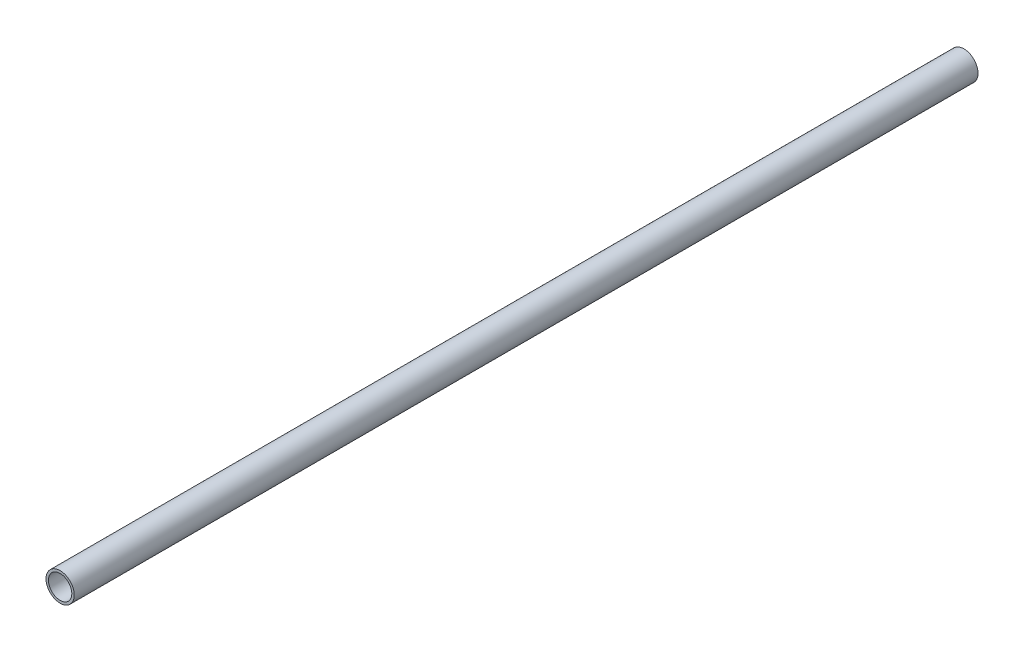
SolidWorks part; units mm, degrees
ref_plane "Front Plane" through (0, 0, 0) normal (0, 0, 1) x (1, 0, 0)
ref_plane "Top Plane" through (0, 0, 0) normal (0, 1, 0) x (1, 0, 0)
ref_plane "Right Plane" through (0, 0, 0) normal (1, 0, 0) x (0, 0, -1)
sketch "Sketch1" plane through (0, 0, 0) normal (0, 0, 1) x (1, 0, 0)
  line L0 (-9.525, 0) -> (9.525, 0) construction
  line L1 (0, -9.525) -> (0, 9.525) construction
  circle A0 centre (0, 0) radius 9.525
  circle A1 centre (0, 0) radius 7.874
  point P4 (0, 0)
  point P9 (0, 0)
  point P10 (7.874, 0)
  dimension "D1" = 15.748
  dimension "OD" = 19.05
  dimension "Wall Thickness" = 1.651
sketch "Sketch2" plane through (0, 0, 0) normal (1, 0, 0) x (0, 0, -1)
  line L0 (304.8, 9.525) -> (-304.8, 9.525) construction
  line L1 (0, 9.525) -> (0, -9.525) construction
  point P3 (-282.8925, 9.525)
  point P4 (0, 9.525)
  point P5 (282.8925, 9.525)
  dimension "D1" = 21.9075
  dimension "D2" = 21.9075
  dimension "Length" = 609.6
sketch "Sketch3" plane through (0, 0, 0) normal (0, 0, 1) x (1, 0, 0)
  line L0 (0, -9.525) -> (0, 9.525) construction
  circle A0 centre (0, 0) radius 9.525
  circle A1 centre (0, 0) radius 7.874
  circle A2 centre (0, 0) radius 7.874 construction
extrude "Boss-Extrude1" add sketch "Sketch3" along normal mid plane 609.6
equation "\"D1@Boss-Extrude1\" = \"Length@Sketch2\""
equation "\"D1@Sketch2\"=\"OD@Sketch1\"*1.15"
equation "\"D2@Sketch2\"=\"D1@Sketch2\""
